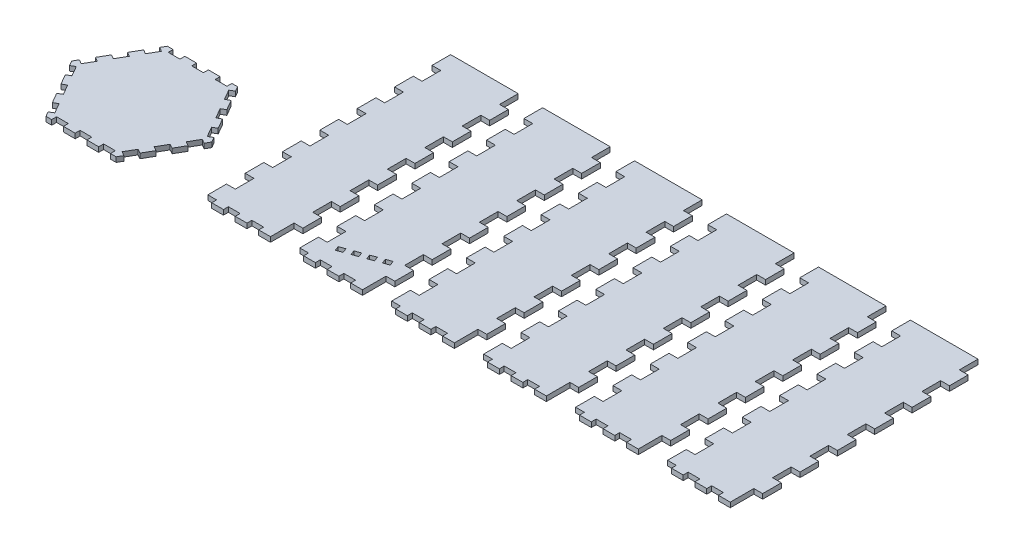
SolidWorks part; units mm, degrees
ref_plane "Front Plane" through (0, 0, 0) normal (0, 0, 1) x (1, 0, 0)
ref_plane "Top Plane" through (0, 0, 0) normal (0, 1, 0) x (1, 0, 0)
ref_plane "Right Plane" through (0, 0, 0) normal (1, 0, 0) x (0, 0, -1)
sketch "Sketch1" plane through (0, 0, 0) normal (0, 1, 0) x (1, 0, 0)
  line L0 (-22.87, -39.612) -> (-19.175, -39.612)
  line L13 (-19.175, -39.612) -> (-19.175, -36.412)
  line L14 (-19.175, -36.412) -> (-11.505, -36.412)
  line L15 (-11.505, -36.412) -> (-11.505, -39.612)
  line L16 (-11.505, -39.612) -> (-3.835, -39.612)
  line L17 (-3.835, -39.612) -> (-3.835, -36.412)
  line L18 (-3.835, -36.412) -> (3.835, -36.412)
  line L19 (3.835, -36.412) -> (3.835, -39.612)
  line L21 (-45.74, 0) -> (-43.8925, -3.2)
  line L22 (3.835, -39.612) -> (11.505, -39.612)
  line L23 (11.505, -39.612) -> (11.505, -36.412)
  line L24 (11.505, -36.412) -> (19.175, -36.412)
  line L25 (19.175, -36.412) -> (19.175, -39.612)
  line L26 (19.175, -39.612) -> (22.87, -39.612)
  line L27 (22.87, -39.612) -> (24.7175, -36.412)
  line L28 (45.74, 0) -> (22.87, 39.612) construction
  line L29 (24.7175, -36.412) -> (21.9462, -34.812)
  line L30 (21.9462, -34.812) -> (25.7812, -28.1696)
  line L31 (25.7812, -28.1696) -> (28.5525, -29.7696)
  line L32 (28.5525, -29.7696) -> (32.3875, -23.1272)
  line L33 (32.3875, -23.1272) -> (29.6162, -21.5272)
  line L34 (29.6162, -21.5272) -> (33.4512, -14.8848)
  line L35 (33.4512, -14.8848) -> (36.2225, -16.4848)
  line L36 (36.2225, -16.4848) -> (40.0575, -9.8424)
  line L37 (40.0575, -9.8424) -> (37.2862, -8.2424)
  line L38 (37.2862, -8.2424) -> (41.1212, -1.6)
  line L39 (41.1212, -1.6) -> (43.8925, -3.2)
  line L40 (43.8925, -3.2) -> (45.74, 0)
  line L41 (45.74, 0) -> (43.8925, 3.2)
  line L42 (22.87, 39.612) -> (-22.87, 39.612) construction
  line L43 (-22.87, 39.612) -> (-45.74, 0) construction
  line L44 (43.8925, 3.2) -> (41.1212, 1.6)
  line L45 (41.1212, 1.6) -> (37.2862, 8.2424)
  line L46 (37.2862, 8.2424) -> (40.0575, 9.8424)
  line L47 (40.0575, 9.8424) -> (36.2225, 16.4848)
  line L48 (36.2225, 16.4848) -> (33.4512, 14.8848)
  line L49 (33.4512, 14.8848) -> (29.6162, 21.5272)
  line L50 (29.6162, 21.5272) -> (32.3875, 23.1272)
  line L51 (32.3875, 23.1272) -> (28.5525, 29.7696)
  line L52 (28.5525, 29.7696) -> (25.7812, 28.1696)
  line L53 (25.7812, 28.1696) -> (21.9462, 34.812)
  line L54 (21.9462, 34.812) -> (24.7175, 36.412)
  line L55 (24.7175, 36.412) -> (22.87, 39.612)
  line L56 (22.87, 39.612) -> (19.175, 39.612)
  line L57 (-45.74, 0) -> (-22.87, -39.612) construction
  line L58 (-22.87, -39.612) -> (22.87, -39.612) construction
  line L59 (19.175, 39.612) -> (19.175, 36.412)
  line L60 (19.175, 36.412) -> (11.505, 36.412)
  line L61 (11.505, 36.412) -> (11.505, 39.612)
  line L62 (11.505, 39.612) -> (3.835, 39.612)
  line L63 (3.835, 39.612) -> (3.835, 36.412)
  line L64 (3.835, 36.412) -> (-3.835, 36.412)
  line L65 (-3.835, 36.412) -> (-3.835, 39.612)
  line L66 (-3.835, 39.612) -> (-11.505, 39.612)
  line L67 (-11.505, 39.612) -> (-11.505, 36.412)
  line L68 (-11.505, 36.412) -> (-19.175, 36.412)
  line L69 (-19.175, 36.412) -> (-19.175, 39.612)
  line L70 (-19.175, 39.612) -> (-22.87, 39.612)
  line L71 (-22.87, 39.612) -> (-24.7175, 36.412)
  line L72 (22.87, -39.612) -> (45.74, 0) construction
  line L73 (-43.8925, -3.2) -> (-41.1212, -1.6)
  line L74 (-24.7175, 36.412) -> (-21.9462, 34.812)
  line L75 (-21.9462, 34.812) -> (-25.7812, 28.1696)
  line L76 (-25.7812, 28.1696) -> (-28.5525, 29.7696)
  line L77 (-28.5525, 29.7696) -> (-32.3875, 23.1272)
  line L78 (-32.3875, 23.1272) -> (-29.6162, 21.5272)
  line L79 (-29.6162, 21.5272) -> (-33.4512, 14.8848)
  line L80 (-33.4512, 14.8848) -> (-36.2225, 16.4848)
  line L81 (-36.2225, 16.4848) -> (-40.0575, 9.8424)
  line L82 (-40.0575, 9.8424) -> (-37.2862, 8.2424)
  line L83 (-37.2862, 8.2424) -> (-41.1212, 1.6)
  line L84 (-41.1212, 1.6) -> (-43.8925, 3.2)
  line L85 (-43.8925, 3.2) -> (-45.74, 0)
  line L86 (-41.1212, -1.6) -> (-37.2862, -8.2424)
  line L87 (-37.2862, -8.2424) -> (-40.0575, -9.8424)
  line L88 (-40.0575, -9.8424) -> (-36.2225, -16.4848)
  line L89 (-36.2225, -16.4848) -> (-33.4512, -14.8848)
  line L90 (-33.4512, -14.8848) -> (-29.6162, -21.5272)
  line L91 (-29.6162, -21.5272) -> (-32.3875, -23.1272)
  line L92 (-32.3875, -23.1272) -> (-28.5525, -29.7696)
  line L93 (-28.5525, -29.7696) -> (-25.7812, -28.1696)
  line L94 (-25.7812, -28.1696) -> (-21.9462, -34.812)
  line L95 (-21.9462, -34.812) -> (-24.7175, -36.412)
  line L96 (-24.7175, -36.412) -> (-22.87, -39.612)
  line L97 (-21.9462, -34.812) -> (-19.175, -39.612) construction
  line L102 (19.175, -36.412) -> (24.7175, -36.412) construction
  line L103 (-19.175, -36.412) -> (-24.7175, -36.412) construction
  line L104 (80.0182, -34.385) -> (87.6882, -34.385)
  line L105 (87.6882, -34.385) -> (87.6882, -31.185)
  line L106 (87.6882, -31.185) -> (95.3582, -31.185)
  line L107 (95.3582, -31.185) -> (95.3582, -34.385)
  line L108 (95.3582, -34.385) -> (103.0282, -34.385)
  line L109 (103.0282, -34.385) -> (103.0282, -31.185)
  line L110 (103.0282, -31.185) -> (110.6981, -31.185)
  line L111 (110.6981, -31.185) -> (110.6981, -34.385)
  line L112 (110.6981, -34.385) -> (118.3681, -34.385)
  line L113 (80.0182, -34.385) -> (80.0182, -31.185)
  line L114 (80.0182, -31.185) -> (74.2756, -31.185)
  line L115 (74.2756, -31.185) -> (74.2756, -18.9967)
  line L116 (74.2756, -18.9967) -> (80.0182, -18.9967)
  line L117 (80.0182, -18.9967) -> (80.0182, -6.8084)
  line L118 (80.0182, -6.8084) -> (74.2756, -6.8084)
  line L121 (118.3681, -6.8084) -> (124.1107, -6.8084)
  line L122 (124.1107, -6.8084) -> (124.1107, -18.9967)
  line L123 (124.1107, -18.9967) -> (118.3681, -18.9967)
  line L124 (118.3681, -18.9967) -> (118.3681, -34.385)
  line L126 (21.9462, -34.812) -> (19.175, -39.612) construction
  line L250 (140.0182, -34.385) -> (147.6882, -34.385)
  line L265 (147.6882, -34.385) -> (147.6882, -31.185)
  line L266 (147.6882, -31.185) -> (155.3582, -31.185)
  line L267 (155.3582, -31.185) -> (155.3582, -34.385)
  line L268 (155.3582, -34.385) -> (163.0282, -34.385)
  line L269 (163.0282, -34.385) -> (163.0282, -31.185)
  line L270 (74.2756, -6.8084) -> (74.2756, 5.3799)
  line L271 (74.2756, 5.3799) -> (80.0182, 5.3799)
  line L272 (80.0182, 5.3799) -> (80.0182, 17.5682)
  line L273 (80.0182, 17.5682) -> (74.2756, 17.5682)
  line L274 (74.2756, 17.5682) -> (74.2756, 29.7565)
  line L275 (74.2756, 29.7565) -> (80.0182, 29.7565)
  line L276 (80.0182, 29.7565) -> (80.0182, 41.9448)
  line L277 (80.0182, 41.9448) -> (74.2756, 41.9448)
  line L278 (74.2756, 41.9448) -> (74.2756, 54.1331)
  line L279 (74.2756, 54.1331) -> (80.0182, 54.1331)
  line L280 (80.0182, 54.1331) -> (80.0182, 66.3215)
  line L281 (80.0182, 66.3215) -> (74.2756, 66.3215)
  line L282 (74.2756, 66.3215) -> (74.2756, 78.5098)
  line L283 (74.2756, 78.5098) -> (80.0182, 78.5098)
  line L284 (80.0182, 78.5098) -> (80.0182, 90.6981)
  line L285 (80.0182, 90.6981) -> (74.2756, 90.6981)
  line L286 (74.2756, 90.6981) -> (74.2756, 102.8864)
  line L287 (74.2756, 102.8864) -> (80.0182, 102.8864)
  line L288 (80.0182, 102.8864) -> (80.0182, 115.0747)
  line L289 (80.0182, 115.0747) -> (74.2756, 115.0747)
  line L290 (74.2756, 115.0747) -> (74.2756, 127.263)
  line L291 (118.3681, -6.8084) -> (118.3681, 5.3799)
  line L292 (118.3681, 5.3799) -> (124.1107, 5.3799)
  line L293 (124.1107, 5.3799) -> (124.1107, 17.5682)
  line L294 (124.1107, 17.5682) -> (118.3681, 17.5682)
  line L295 (118.3681, 17.5682) -> (118.3681, 29.7565)
  line L296 (118.3681, 29.7565) -> (124.1107, 29.7565)
  line L297 (124.1107, 29.7565) -> (124.1107, 41.9448)
  line L298 (124.1107, 41.9448) -> (118.3681, 41.9448)
  line L299 (118.3681, 41.9448) -> (118.3681, 54.1331)
  line L300 (118.3681, 54.1331) -> (124.1107, 54.1331)
  line L301 (124.1107, 54.1331) -> (124.1107, 66.3215)
  line L302 (124.1107, 66.3215) -> (118.3681, 66.3215)
  line L303 (118.3681, 66.3215) -> (118.3681, 78.5098)
  line L304 (118.3681, 78.5098) -> (124.1107, 78.5098)
  line L305 (124.1107, 78.5098) -> (124.1107, 90.6981)
  line L306 (124.1107, 90.6981) -> (118.3681, 90.6981)
  line L307 (118.3681, 90.6981) -> (118.3681, 102.8864)
  line L308 (118.3681, 102.8864) -> (124.1107, 102.8864)
  line L309 (124.1107, 102.8864) -> (124.1107, 115.0747)
  line L310 (124.1107, 115.0747) -> (118.3681, 115.0747)
  line L311 (118.3681, 115.0747) -> (118.3681, 127.263)
  line L312 (163.0282, -31.185) -> (170.6981, -31.185)
  line L313 (170.6981, -31.185) -> (170.6981, -34.385)
  line L314 (170.6981, -34.385) -> (178.3681, -34.385)
  line L315 (140.0182, -34.385) -> (140.0182, -31.185)
  line L316 (140.0182, -31.185) -> (134.2756, -31.185)
  line L317 (134.2756, -31.185) -> (134.2756, -18.9967)
  line L318 (134.2756, -18.9967) -> (140.0182, -18.9967)
  line L319 (140.0182, -18.9967) -> (140.0182, -6.8084)
  line L320 (140.0182, -6.8084) -> (134.2756, -6.8084)
  line L322 (178.3681, -6.8084) -> (184.1107, -6.8084)
  line L323 (184.1107, -6.8084) -> (184.1107, -18.9967)
  line L324 (184.1107, -18.9967) -> (178.3681, -18.9967)
  line L325 (178.3681, -18.9967) -> (178.3681, -34.385)
  line L326 (134.2756, -6.8084) -> (134.2756, 5.3799)
  line L327 (134.2756, 5.3799) -> (140.0182, 5.3799)
  line L328 (140.0182, 5.3799) -> (140.0182, 17.5682)
  line L329 (140.0182, 17.5682) -> (134.2756, 17.5682)
  line L330 (134.2756, 17.5682) -> (134.2756, 29.7565)
  line L331 (134.2756, 29.7565) -> (140.0182, 29.7565)
  line L332 (140.0182, 29.7565) -> (140.0182, 41.9448)
  line L333 (140.0182, 41.9448) -> (134.2756, 41.9448)
  line L334 (134.2756, 41.9448) -> (134.2756, 54.1331)
  line L335 (134.2756, 54.1331) -> (140.0182, 54.1331)
  line L336 (140.0182, 54.1331) -> (140.0182, 66.3215)
  line L337 (140.0182, 66.3215) -> (134.2756, 66.3215)
  line L338 (134.2756, 66.3215) -> (134.2756, 78.5098)
  line L339 (134.2756, 78.5098) -> (140.0182, 78.5098)
  line L340 (140.0182, 78.5098) -> (140.0182, 90.6981)
  line L341 (140.0182, 90.6981) -> (134.2756, 90.6981)
  line L342 (134.2756, 90.6981) -> (134.2756, 102.8864)
  line L343 (134.2756, 102.8864) -> (140.0182, 102.8864)
  line L344 (140.0182, 102.8864) -> (140.0182, 115.0747)
  line L345 (140.0182, 115.0747) -> (134.2756, 115.0747)
  line L346 (134.2756, 115.0747) -> (134.2756, 127.263)
  line L347 (178.3681, -6.8084) -> (178.3681, 5.3799)
  line L348 (178.3681, 5.3799) -> (184.1107, 5.3799)
  line L349 (184.1107, 5.3799) -> (184.1107, 17.5682)
  line L350 (184.1107, 17.5682) -> (178.3681, 17.5682)
  line L351 (178.3681, 17.5682) -> (178.3681, 29.7565)
  line L352 (178.3681, 29.7565) -> (184.1107, 29.7565)
  line L353 (184.1107, 29.7565) -> (184.1107, 41.9448)
  line L354 (184.1107, 41.9448) -> (178.3681, 41.9448)
  line L355 (178.3681, 41.9448) -> (178.3681, 54.1331)
  line L356 (178.3681, 54.1331) -> (184.1107, 54.1331)
  line L357 (184.1107, 54.1331) -> (184.1107, 66.3215)
  line L358 (184.1107, 66.3215) -> (178.3681, 66.3215)
  line L359 (178.3681, 66.3215) -> (178.3681, 78.5098)
  line L360 (178.3681, 78.5098) -> (184.1107, 78.5098)
  line L361 (184.1107, 78.5098) -> (184.1107, 90.6981)
  line L362 (184.1107, 90.6981) -> (178.3681, 90.6981)
  line L363 (178.3681, 90.6981) -> (178.3681, 102.8864)
  line L364 (178.3681, 102.8864) -> (184.1107, 102.8864)
  line L365 (184.1107, 102.8864) -> (184.1107, 115.0747)
  line L366 (184.1107, 115.0747) -> (178.3681, 115.0747)
  line L367 (178.3681, 115.0747) -> (178.3681, 127.263)
  line L369 (200.0182, -34.385) -> (207.6882, -34.385)
  line L370 (207.6882, -34.385) -> (207.6882, -31.185)
  line L371 (207.6882, -31.185) -> (215.3582, -31.185)
  line L372 (215.3582, -31.185) -> (215.3582, -34.385)
  line L373 (215.3582, -34.385) -> (223.0282, -34.385)
  line L374 (223.0282, -34.385) -> (223.0282, -31.185)
  line L375 (223.0282, -31.185) -> (230.6981, -31.185)
  line L376 (230.6981, -31.185) -> (230.6981, -34.385)
  line L377 (230.6981, -34.385) -> (238.3681, -34.385)
  line L378 (200.0182, -34.385) -> (200.0182, -31.185)
  line L379 (200.0182, -31.185) -> (194.2756, -31.185)
  line L380 (194.2756, -31.185) -> (194.2756, -18.9967)
  line L381 (194.2756, -18.9967) -> (200.0182, -18.9967)
  line L382 (200.0182, -18.9967) -> (200.0182, -6.8084)
  line L383 (200.0182, -6.8084) -> (194.2756, -6.8084)
  line L385 (238.3681, -6.8084) -> (244.1107, -6.8084)
  line L386 (244.1107, -6.8084) -> (244.1107, -18.9967)
  line L387 (244.1107, -18.9967) -> (238.3681, -18.9967)
  line L388 (238.3681, -18.9967) -> (238.3681, -34.385)
  line L389 (194.2756, -6.8084) -> (194.2756, 5.3799)
  line L390 (194.2756, 5.3799) -> (200.0182, 5.3799)
  line L391 (200.0182, 5.3799) -> (200.0182, 17.5682)
  line L392 (200.0182, 17.5682) -> (194.2756, 17.5682)
  line L393 (194.2756, 17.5682) -> (194.2756, 29.7565)
  line L394 (194.2756, 29.7565) -> (200.0182, 29.7565)
  line L395 (200.0182, 29.7565) -> (200.0182, 41.9448)
  line L396 (200.0182, 41.9448) -> (194.2756, 41.9448)
  line L397 (194.2756, 41.9448) -> (194.2756, 54.1331)
  line L398 (194.2756, 54.1331) -> (200.0182, 54.1331)
  line L399 (200.0182, 54.1331) -> (200.0182, 66.3215)
  line L400 (200.0182, 66.3215) -> (194.2756, 66.3215)
  line L401 (194.2756, 66.3215) -> (194.2756, 78.5098)
  line L402 (194.2756, 78.5098) -> (200.0182, 78.5098)
  line L403 (200.0182, 78.5098) -> (200.0182, 90.6981)
  line L404 (200.0182, 90.6981) -> (194.2756, 90.6981)
  line L405 (194.2756, 90.6981) -> (194.2756, 102.8864)
  line L406 (194.2756, 102.8864) -> (200.0182, 102.8864)
  line L407 (200.0182, 102.8864) -> (200.0182, 115.0747)
  line L408 (200.0182, 115.0747) -> (194.2756, 115.0747)
  line L409 (194.2756, 115.0747) -> (194.2756, 127.263)
  line L410 (238.3681, -6.8084) -> (238.3681, 5.3799)
  line L411 (238.3681, 5.3799) -> (244.1107, 5.3799)
  line L412 (244.1107, 5.3799) -> (244.1107, 17.5682)
  line L413 (244.1107, 17.5682) -> (238.3681, 17.5682)
  line L414 (238.3681, 17.5682) -> (238.3681, 29.7565)
  line L415 (238.3681, 29.7565) -> (244.1107, 29.7565)
  line L416 (244.1107, 29.7565) -> (244.1107, 41.9448)
  line L417 (244.1107, 41.9448) -> (238.3681, 41.9448)
  line L418 (238.3681, 41.9448) -> (238.3681, 54.1331)
  line L419 (238.3681, 54.1331) -> (244.1107, 54.1331)
  line L420 (244.1107, 54.1331) -> (244.1107, 66.3215)
  line L421 (244.1107, 66.3215) -> (238.3681, 66.3215)
  line L422 (238.3681, 66.3215) -> (238.3681, 78.5098)
  line L423 (238.3681, 78.5098) -> (244.1107, 78.5098)
  line L424 (244.1107, 78.5098) -> (244.1107, 90.6981)
  line L425 (244.1107, 90.6981) -> (238.3681, 90.6981)
  line L426 (238.3681, 90.6981) -> (238.3681, 102.8864)
  line L427 (238.3681, 102.8864) -> (244.1107, 102.8864)
  line L428 (244.1107, 102.8864) -> (244.1107, 115.0747)
  line L429 (244.1107, 115.0747) -> (238.3681, 115.0747)
  line L430 (238.3681, 115.0747) -> (238.3681, 127.263)
  line L432 (260.0182, -34.385) -> (267.6882, -34.385)
  line L433 (267.6882, -34.385) -> (267.6882, -31.185)
  line L434 (267.6882, -31.185) -> (275.3582, -31.185)
  line L435 (275.3582, -31.185) -> (275.3582, -34.385)
  line L436 (275.3582, -34.385) -> (283.0282, -34.385)
  line L437 (283.0282, -34.385) -> (283.0282, -31.185)
  line L438 (283.0282, -31.185) -> (290.6981, -31.185)
  line L439 (290.6981, -31.185) -> (290.6981, -34.385)
  line L440 (290.6981, -34.385) -> (298.3681, -34.385)
  line L441 (260.0182, -34.385) -> (260.0182, -31.185)
  line L442 (260.0182, -31.185) -> (254.2756, -31.185)
  line L443 (254.2756, -31.185) -> (254.2756, -18.9967)
  line L444 (254.2756, -18.9967) -> (260.0182, -18.9967)
  line L445 (260.0182, -18.9967) -> (260.0182, -6.8084)
  line L446 (260.0182, -6.8084) -> (254.2756, -6.8084)
  line L448 (298.3681, -6.8084) -> (304.1107, -6.8084)
  line L449 (304.1107, -6.8084) -> (304.1107, -18.9967)
  line L450 (304.1107, -18.9967) -> (298.3681, -18.9967)
  line L451 (298.3681, -18.9967) -> (298.3681, -34.385)
  line L452 (254.2756, -6.8084) -> (254.2756, 5.3799)
  line L453 (254.2756, 5.3799) -> (260.0182, 5.3799)
  line L454 (260.0182, 5.3799) -> (260.0182, 17.5682)
  line L455 (260.0182, 17.5682) -> (254.2756, 17.5682)
  line L456 (254.2756, 17.5682) -> (254.2756, 29.7565)
  line L457 (254.2756, 29.7565) -> (260.0182, 29.7565)
  line L458 (260.0182, 29.7565) -> (260.0182, 41.9448)
  line L459 (260.0182, 41.9448) -> (254.2756, 41.9448)
  line L460 (254.2756, 41.9448) -> (254.2756, 54.1331)
  line L461 (254.2756, 54.1331) -> (260.0182, 54.1331)
  line L462 (260.0182, 54.1331) -> (260.0182, 66.3215)
  line L463 (260.0182, 66.3215) -> (254.2756, 66.3215)
  line L464 (254.2756, 66.3215) -> (254.2756, 78.5098)
  line L465 (254.2756, 78.5098) -> (260.0182, 78.5098)
  line L466 (260.0182, 78.5098) -> (260.0182, 90.6981)
  line L467 (260.0182, 90.6981) -> (254.2756, 90.6981)
  line L468 (254.2756, 90.6981) -> (254.2756, 102.8864)
  line L469 (254.2756, 102.8864) -> (260.0182, 102.8864)
  line L470 (260.0182, 102.8864) -> (260.0182, 115.0747)
  line L471 (260.0182, 115.0747) -> (254.2756, 115.0747)
  line L472 (254.2756, 115.0747) -> (254.2756, 127.263)
  line L473 (298.3681, -6.8084) -> (298.3681, 5.3799)
  line L474 (298.3681, 5.3799) -> (304.1107, 5.3799)
  line L475 (304.1107, 5.3799) -> (304.1107, 17.5682)
  line L476 (304.1107, 17.5682) -> (298.3681, 17.5682)
  line L477 (298.3681, 17.5682) -> (298.3681, 29.7565)
  line L478 (298.3681, 29.7565) -> (304.1107, 29.7565)
  line L479 (304.1107, 29.7565) -> (304.1107, 41.9448)
  line L480 (304.1107, 41.9448) -> (298.3681, 41.9448)
  line L481 (298.3681, 41.9448) -> (298.3681, 54.1331)
  line L482 (298.3681, 54.1331) -> (304.1107, 54.1331)
  line L483 (304.1107, 54.1331) -> (304.1107, 66.3215)
  line L484 (304.1107, 66.3215) -> (298.3681, 66.3215)
  line L485 (298.3681, 66.3215) -> (298.3681, 78.5098)
  line L486 (298.3681, 78.5098) -> (304.1107, 78.5098)
  line L487 (304.1107, 78.5098) -> (304.1107, 90.6981)
  line L488 (304.1107, 90.6981) -> (298.3681, 90.6981)
  line L489 (298.3681, 90.6981) -> (298.3681, 102.8864)
  line L490 (298.3681, 102.8864) -> (304.1107, 102.8864)
  line L491 (304.1107, 102.8864) -> (304.1107, 115.0747)
  line L492 (304.1107, 115.0747) -> (298.3681, 115.0747)
  line L493 (298.3681, 115.0747) -> (298.3681, 127.263)
  line L495 (320.0182, -34.385) -> (327.6882, -34.385)
  line L496 (327.6882, -34.385) -> (327.6882, -31.185)
  line L497 (327.6882, -31.185) -> (335.3582, -31.185)
  line L498 (335.3582, -31.185) -> (335.3582, -34.385)
  line L499 (335.3582, -34.385) -> (343.0282, -34.385)
  line L500 (343.0282, -34.385) -> (343.0282, -31.185)
  line L501 (343.0282, -31.185) -> (350.6981, -31.185)
  line L502 (350.6981, -31.185) -> (350.6981, -34.385)
  line L503 (350.6981, -34.385) -> (358.3681, -34.385)
  line L504 (320.0182, -34.385) -> (320.0182, -31.185)
  line L505 (320.0182, -31.185) -> (314.2756, -31.185)
  line L506 (314.2756, -31.185) -> (314.2756, -18.9967)
  line L507 (314.2756, -18.9967) -> (320.0182, -18.9967)
  line L508 (320.0182, -18.9967) -> (320.0182, -6.8084)
  line L509 (320.0182, -6.8084) -> (314.2756, -6.8084)
  line L511 (358.3681, -6.8084) -> (364.1107, -6.8084)
  line L512 (364.1107, -6.8084) -> (364.1107, -18.9967)
  line L513 (364.1107, -18.9967) -> (358.3681, -18.9967)
  line L514 (358.3681, -18.9967) -> (358.3681, -34.385)
  line L515 (314.2756, -6.8084) -> (314.2756, 5.3799)
  line L516 (314.2756, 5.3799) -> (320.0182, 5.3799)
  line L517 (320.0182, 5.3799) -> (320.0182, 17.5682)
  line L518 (320.0182, 17.5682) -> (314.2756, 17.5682)
  line L519 (314.2756, 17.5682) -> (314.2756, 29.7565)
  line L520 (314.2756, 29.7565) -> (320.0182, 29.7565)
  line L521 (320.0182, 29.7565) -> (320.0182, 41.9448)
  line L522 (320.0182, 41.9448) -> (314.2756, 41.9448)
  line L523 (314.2756, 41.9448) -> (314.2756, 54.1331)
  line L524 (314.2756, 54.1331) -> (320.0182, 54.1331)
  line L525 (320.0182, 54.1331) -> (320.0182, 66.3215)
  line L526 (320.0182, 66.3215) -> (314.2756, 66.3215)
  line L527 (314.2756, 66.3215) -> (314.2756, 78.5098)
  line L528 (314.2756, 78.5098) -> (320.0182, 78.5098)
  line L529 (320.0182, 78.5098) -> (320.0182, 90.6981)
  line L530 (320.0182, 90.6981) -> (314.2756, 90.6981)
  line L531 (314.2756, 90.6981) -> (314.2756, 102.8864)
  line L532 (314.2756, 102.8864) -> (320.0182, 102.8864)
  line L533 (320.0182, 102.8864) -> (320.0182, 115.0747)
  line L534 (320.0182, 115.0747) -> (314.2756, 115.0747)
  line L535 (314.2756, 115.0747) -> (314.2756, 127.263)
  line L536 (358.3681, -6.8084) -> (358.3681, 5.3799)
  line L537 (358.3681, 5.3799) -> (364.1107, 5.3799)
  line L538 (364.1107, 5.3799) -> (364.1107, 17.5682)
  line L539 (364.1107, 17.5682) -> (358.3681, 17.5682)
  line L540 (358.3681, 17.5682) -> (358.3681, 29.7565)
  line L541 (358.3681, 29.7565) -> (364.1107, 29.7565)
  line L542 (364.1107, 29.7565) -> (364.1107, 41.9448)
  line L543 (364.1107, 41.9448) -> (358.3681, 41.9448)
  line L544 (358.3681, 41.9448) -> (358.3681, 54.1331)
  line L545 (358.3681, 54.1331) -> (364.1107, 54.1331)
  line L546 (364.1107, 54.1331) -> (364.1107, 66.3215)
  line L547 (364.1107, 66.3215) -> (358.3681, 66.3215)
  line L548 (358.3681, 66.3215) -> (358.3681, 78.5098)
  line L549 (358.3681, 78.5098) -> (364.1107, 78.5098)
  line L550 (364.1107, 78.5098) -> (364.1107, 90.6981)
  line L551 (364.1107, 90.6981) -> (358.3681, 90.6981)
  line L552 (358.3681, 90.6981) -> (358.3681, 102.8864)
  line L553 (358.3681, 102.8864) -> (364.1107, 102.8864)
  line L554 (364.1107, 102.8864) -> (364.1107, 115.0747)
  line L555 (364.1107, 115.0747) -> (358.3681, 115.0747)
  line L556 (358.3681, 115.0747) -> (358.3681, 127.263)
  line L558 (380.0182, -34.385) -> (387.6882, -34.385)
  line L559 (387.6882, -34.385) -> (387.6882, -31.185)
  line L560 (387.6882, -31.185) -> (395.3582, -31.185)
  line L561 (395.3582, -31.185) -> (395.3582, -34.385)
  line L562 (395.3582, -34.385) -> (403.0282, -34.385)
  line L563 (403.0282, -34.385) -> (403.0282, -31.185)
  line L564 (403.0282, -31.185) -> (410.6981, -31.185)
  line L565 (410.6981, -31.185) -> (410.6981, -34.385)
  line L566 (410.6981, -34.385) -> (418.3681, -34.385)
  line L567 (380.0182, -34.385) -> (380.0182, -31.185)
  line L568 (380.0182, -31.185) -> (374.2756, -31.185)
  line L569 (374.2756, -31.185) -> (374.2756, -18.9967)
  line L570 (374.2756, -18.9967) -> (380.0182, -18.9967)
  line L571 (380.0182, -18.9967) -> (380.0182, -6.8084)
  line L572 (380.0182, -6.8084) -> (374.2756, -6.8084)
  line L574 (418.3681, -6.8084) -> (424.1107, -6.8084)
  line L575 (424.1107, -6.8084) -> (424.1107, -18.9967)
  line L576 (424.1107, -18.9967) -> (418.3681, -18.9967)
  line L577 (418.3681, -18.9967) -> (418.3681, -34.385)
  line L578 (374.2756, -6.8084) -> (374.2756, 5.3799)
  line L579 (374.2756, 5.3799) -> (380.0182, 5.3799)
  line L580 (380.0182, 5.3799) -> (380.0182, 17.5682)
  line L581 (380.0182, 17.5682) -> (374.2756, 17.5682)
  line L582 (374.2756, 17.5682) -> (374.2756, 29.7565)
  line L583 (374.2756, 29.7565) -> (380.0182, 29.7565)
  line L584 (380.0182, 29.7565) -> (380.0182, 41.9448)
  line L585 (380.0182, 41.9448) -> (374.2756, 41.9448)
  line L586 (374.2756, 41.9448) -> (374.2756, 54.1331)
  line L587 (374.2756, 54.1331) -> (380.0182, 54.1331)
  line L588 (380.0182, 54.1331) -> (380.0182, 66.3215)
  line L589 (380.0182, 66.3215) -> (374.2756, 66.3215)
  line L590 (374.2756, 66.3215) -> (374.2756, 78.5098)
  line L591 (374.2756, 78.5098) -> (380.0182, 78.5098)
  line L592 (380.0182, 78.5098) -> (380.0182, 90.6981)
  line L593 (380.0182, 90.6981) -> (374.2756, 90.6981)
  line L594 (374.2756, 90.6981) -> (374.2756, 102.8864)
  line L595 (374.2756, 102.8864) -> (380.0182, 102.8864)
  line L596 (380.0182, 102.8864) -> (380.0182, 115.0747)
  line L597 (380.0182, 115.0747) -> (374.2756, 115.0747)
  line L598 (374.2756, 115.0747) -> (374.2756, 127.263)
  line L599 (418.3681, -6.8084) -> (418.3681, 5.3799)
  line L600 (418.3681, 5.3799) -> (424.1107, 5.3799)
  line L601 (424.1107, 5.3799) -> (424.1107, 17.5682)
  line L602 (424.1107, 17.5682) -> (418.3681, 17.5682)
  line L603 (418.3681, 17.5682) -> (418.3681, 29.7565)
  line L604 (418.3681, 29.7565) -> (424.1107, 29.7565)
  line L605 (424.1107, 29.7565) -> (424.1107, 41.9448)
  line L606 (424.1107, 41.9448) -> (418.3681, 41.9448)
  line L607 (418.3681, 41.9448) -> (418.3681, 54.1331)
  line L608 (418.3681, 54.1331) -> (424.1107, 54.1331)
  line L609 (424.1107, 54.1331) -> (424.1107, 66.3215)
  line L610 (424.1107, 66.3215) -> (418.3681, 66.3215)
  line L611 (418.3681, 66.3215) -> (418.3681, 78.5098)
  line L612 (418.3681, 78.5098) -> (424.1107, 78.5098)
  line L613 (424.1107, 78.5098) -> (424.1107, 90.6981)
  line L614 (424.1107, 90.6981) -> (418.3681, 90.6981)
  line L615 (418.3681, 90.6981) -> (418.3681, 102.8864)
  line L616 (418.3681, 102.8864) -> (424.1107, 102.8864)
  line L617 (424.1107, 102.8864) -> (424.1107, 115.0747)
  line L618 (424.1107, 115.0747) -> (418.3681, 115.0747)
  line L619 (418.3681, 115.0747) -> (418.3681, 127.263)
  line L620 (161.1261, -12.4487) -> (164.8848, -11.0806)
  line L621 (146.091, -17.921) -> (149.8498, -16.5529)
  line L622 (146.091, -17.921) -> (147.1854, -20.928)
  line L623 (147.1854, -20.928) -> (150.9442, -19.5599)
  line L624 (149.8498, -16.5529) -> (150.9442, -19.5599)
  line L625 (153.6085, -15.1848) -> (157.3673, -13.8167)
  line L626 (153.6085, -15.1848) -> (154.703, -18.1918)
  line L627 (154.703, -18.1918) -> (158.4618, -16.8238)
  line L628 (157.3673, -13.8167) -> (158.4618, -16.8238)
  line L629 (161.1261, -12.4487) -> (162.2205, -15.4557)
  line L630 (162.2205, -15.4557) -> (165.9793, -14.0876)
  line L631 (164.8848, -11.0806) -> (165.9793, -14.0876)
  line L632 (168.6436, -9.7125) -> (172.4024, -8.3444)
  line L633 (168.6436, -9.7125) -> (169.7381, -12.7195)
  line L634 (169.7381, -12.7195) -> (173.4968, -11.3514)
  line L635 (172.4024, -8.3444) -> (173.4968, -11.3514)
  line L636 (118.3681, 127.263) -> (74.2756, 127.263)
  line L637 (134.2756, 127.263) -> (178.3681, 127.263)
  line L638 (194.2756, 127.263) -> (238.3681, 127.263)
  line L639 (254.2756, 127.263) -> (298.3681, 127.263)
  line L640 (314.2756, 127.263) -> (358.3681, 127.263)
  line L641 (374.2756, 127.263) -> (418.3681, 127.263)
  circle A0 centre (0, 0) radius 39.612 construction
  dimension "D9" = 79.224
  dimension "D66" = 38.3499
  dimension "D79" = 3.2
  dimension "D10" = 38.3499
  dimension "D83" = 5.7426
  dimension "D45" = 5.7426
  dimension "D12" = 120
  dimension "D2" = 3.695
  dimension "D3" = 7.67
  dimension "D5" = 38.3499
  dimension "D11" = 12.1883
  dimension "D13" = 3.2
  dimension "D14" = 5.5426
  dimension "D86" = 15.3883
  dimension "D16" = 3.2
  dimension "D17" = 4
  dimension "D18" = 4
  dimension "D19" = 4
  dimension "D20" = 4
  dimension "D21" = 70
  dimension "D22" = 158.448
  dimension "D15" = 6
extrude "Boss-Extrude3" add sketch "Sketch1" along normal blind 3.2
equation "\"Thick\"=3.2"
equation "\"D79@Sketch1\"=\"Thick\""
equation "\"D10@Sketch1\"=\"D5@Sketch1\""
equation "\"angletabwidth\"=4"
equation "\"D22@Sketch1\"=\"D9@Sketch1\"*2"
